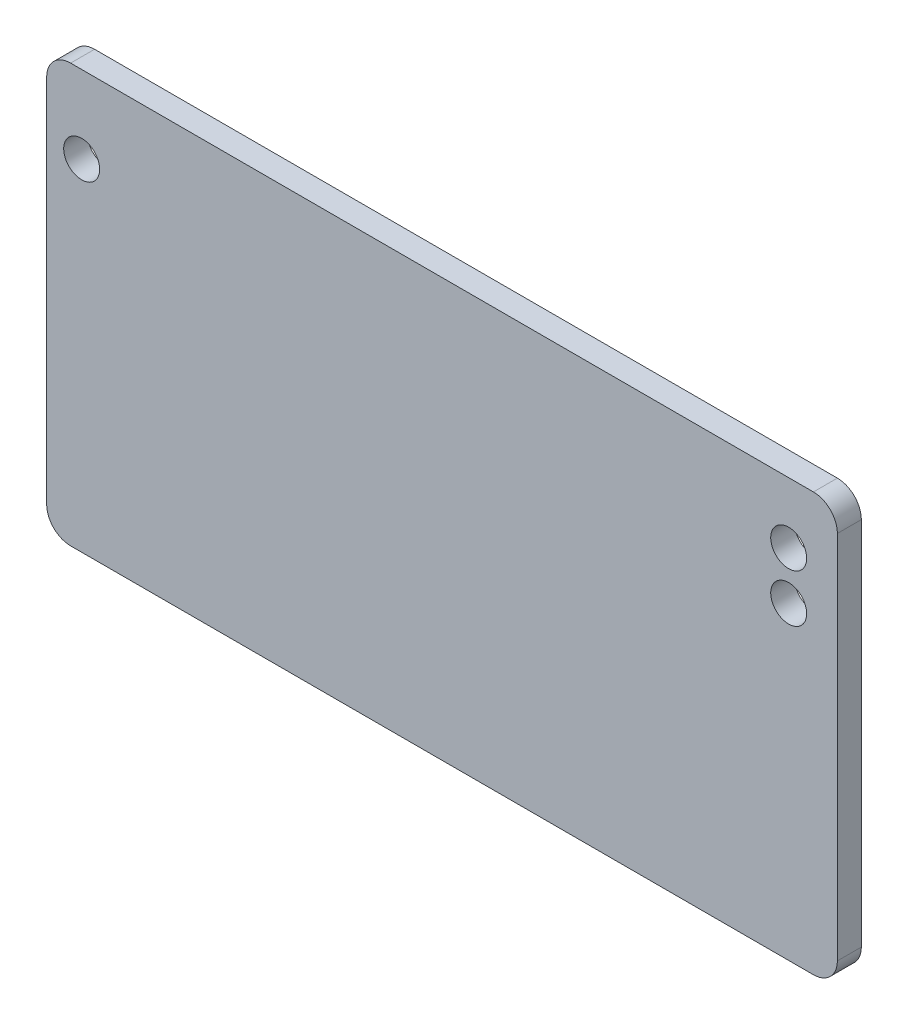
SolidWorks part; units mm, degrees
ref_plane "前视基准面" through (0, 0, 0) normal (0, 0, 1) x (1, 0, 0)
ref_plane "上视基准面" through (0, 0, 0) normal (0, 1, 0) x (1, 0, 0)
ref_plane "右视基准面" through (0, 0, 0) normal (1, 0, 0) x (0, 0, -1)
other "Configuration Table"
sketch "草图1" plane through (0, 0, 0) normal (0, 0, 1) x (1, 0, 0)
  line L1 (-30.094, 14.0368) -> (31.906, 14.0368)
  line L2 (-32.094, 12.0368) -> (-32.094, -18.8632)
  line L3 (-30.094, -20.8632) -> (31.906, -20.8632)
  line L4 (33.906, 12.0368) -> (33.906, -18.8632)
  arc A0 (33.906, 12.0368) -> (31.906, 14.0368) centre (31.906, 12.0368) ccw
  arc A1 (31.906, -20.8632) -> (33.906, -18.8632) centre (31.906, -18.8632) ccw
  arc A2 (-30.094, -20.8632) -> (-32.094, -18.8632) centre (-30.094, -18.8632) cw
  arc A3 (-32.094, 12.0368) -> (-30.094, 14.0368) centre (-30.094, 12.0368) cw
  point P6 (33.906, 14.0368)
  point P11 (-32.094, -20.8632)
  point P14 (-32.094, 14.0368)
  dimension "D3" = 2
  dimension "D1" = 34.9
  dimension "D2" = 66
extrude "凸台-拉伸1" add sketch "草图1" along normal blind 2
sketch "草图2" plane through (0, 0, 2) normal (0, 0, 1) x (1, 0, 0)
  line L0 (-32.094, 12.0368) -> (-32.094, -18.8632) construction
  line L1 (31.906, 14.0368) -> (-30.094, 14.0368) construction
  line L2 (33.906, -18.8632) -> (33.906, 12.0368) construction
  circle A0 centre (-29.173, 7.5598) radius 1.5
  circle A1 centre (29.842, 8.9568) radius 1.5
  circle A2 centre (29.842, 4.9568) radius 1.5
  point P0 (-29.173, 7.5598)
  point P1 (29.842, 8.9568)
  point P2 (29.842, 4.9568)
  dimension "D3" = 4.064
  dimension "D1" = 2.921
  dimension "D2" = 6.477
  dimension "D4" = 5.08
  dimension "D5" = 4
extrude "切除-拉伸1" cut sketch "草图2" against normal blind 3
